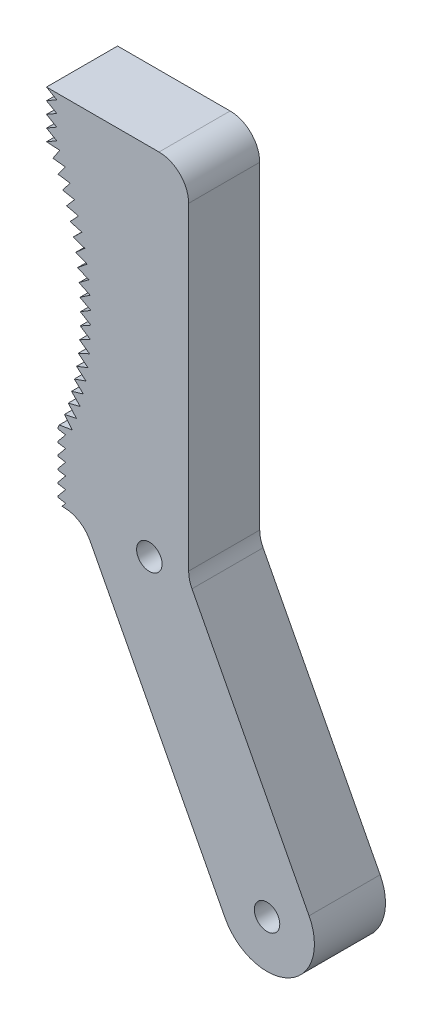
SolidWorks part; units mm, degrees
material "ABS"
ref_plane "Front Plane" through (0, 0, 0) normal (0, 0, 1) x (1, 0, 0)
ref_plane "Top Plane" through (0, 0, 0) normal (0, 1, 0) x (1, 0, 0)
ref_plane "Right Plane" through (0, 0, 0) normal (1, 0, 0) x (0, 0, -1)
sketch "Sketch1" plane through (0, 0, 0) normal (0, 0, 1) x (1, 0, 0)
  line L0 (0, 60) -> (0, 0)
  line L1 (0, 0) -> (20.3305, -39.0214)
  line L2 (6.1409, -46.4143) -> (-18.0414, 0)
  line L5 (-24, 52) -> (-24, 60)
  line L6 (-24, 60) -> (0, 60)
  line L7 (-22.0414, 11.1985) -> (-22.0414, 0)
  line L8 (-22.0414, 0) -> (-18.0414, 0)
  arc A0 (20.3305, -39.0214) -> (6.1409, -46.4143) centre (13.2357, -42.7179) cw
  arc A2 (-24, 52) -> (-22.0414, 11.1985) centre (-66.5155, 29.5113) cw
  circle A4 centre (-6.6369, 0) radius 2.15
  circle A5 centre (13.2357, -42.7179) radius 2.15
  dimension "D4" = 16
  dimension "D7" = 8
  dimension "D8" = 4.3
  dimension "D9" = 4.3
  dimension "D1" = 24
  dimension "D2" = 4
  dimension "D3" = 44
  dimension "D5" = 60
extrude "Boss-Extrude1" add sketch "Sketch1" along normal blind 12
sketch "Sketch2" plane through (0, 0, 12) normal (0, 0, 1) x (1, 0, 0)
  line L0 (-24, 60) -> (-22.2679, 59)
  line L1 (-22.2679, 59) -> (-24, 58)
  line L2 (-24, 52) -> (-24, 60) construction
  line L3 (-24, 58) -> (-24, 60)
  dimension "D1" = 2
extrude "Cut-Extrude1" cut sketch "Sketch2" against normal through all
pattern_linear "LPattern1" count 4 spacing 2 along (0, -1, 0) of "Cut-Extrude1"
fillet "Fillet1" radius 5 3 edges at (0, 60, 6) (-18.0414, 0, 6) (0, 0, 6)
sketch "Sketch3" plane through (0, 0, 12) normal (0, 0, 1) x (1, 0, 0)
  line L0 (-24, 52) -> (-21.7684, 51.8653)
  line L1 (-21.7684, 51.8653) -> (-23.0009, 50)
  line L2 (-23.0009, 50) -> (-24, 52)
  arc A0 (-22.0414, 11.1985) -> (-24, 52) centre (-66.5155, 29.5113) ccw construction
  dimension "D1" = 2
extrude "Cut-Extrude2" cut sketch "Sketch3" against normal through all
pattern_circular "CirPattern1" count 20 over 47 about axis through (-66.5155, 29.5113, 0) along (0, 0, 1) of "Cut-Extrude2"
sketch "Sketch4" plane through (0, 0, 12) normal (0, 0, 1) x (1, 0, 0)
  line L0 (-22.7402, 11.0828) -> (-20.7679, 10.7511)
  line L1 (-20.7679, 10.7511) -> (-22.0414, 9.2089)
  line L2 (-22.0414, 11.1985) -> (-22.0414, 0) construction
  line L3 (-22.0414, 9.2089) -> (-22.7402, 11.0828)
  dimension "D1" = 2
extrude "Cut-Extrude3" cut sketch "Sketch4" against normal through all
pattern_linear "LPattern2" count 8 spacing 2 along (0, -1, 0) of "Cut-Extrude3"
